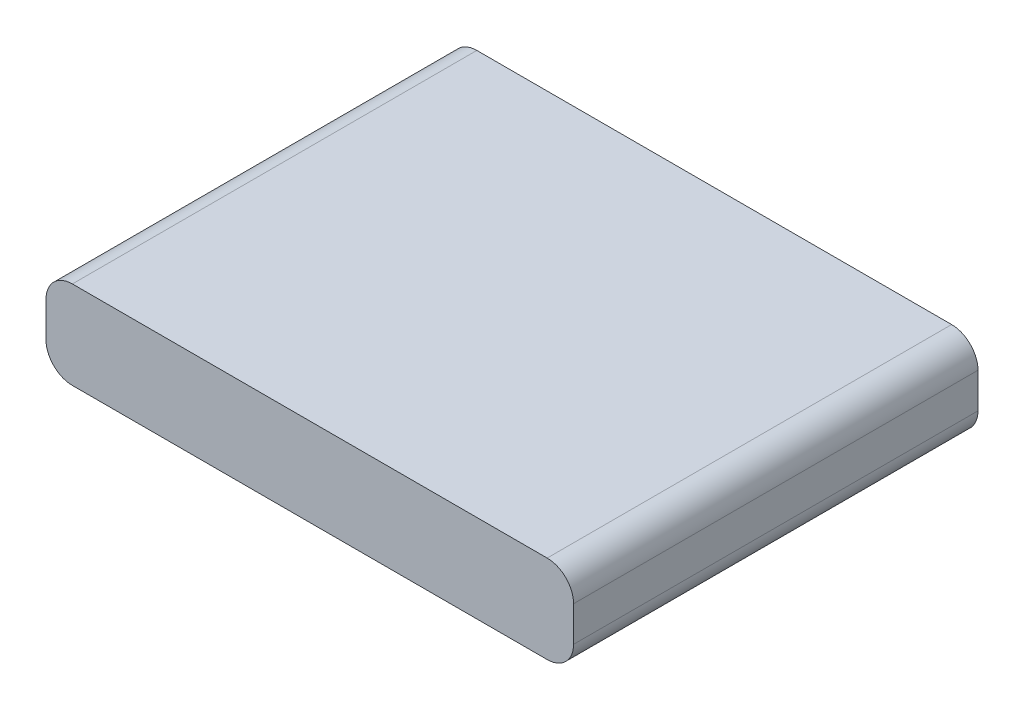
SolidWorks part; units mm, degrees
ref_plane "Front Plane" through (0, 0, 0) normal (0, 0, 1) x (1, 0, 0)
ref_plane "Top Plane" through (0, 0, 0) normal (0, 1, 0) x (1, 0, 0)
ref_plane "Right Plane" through (0, 0, 0) normal (1, 0, 0) x (0, 0, -1)
sketch "Sketch1" plane through (0, 0, 0) normal (0, 0, 1) x (1, 0, 0)
  line L0 (-27, 0) -> (27, 0)
  line L1 (30, 3) -> (30, 7)
  line L2 (27, 10) -> (-27, 10)
  line L3 (-30, 7) -> (-30, 3)
  arc A0 (27, 0) -> (30, 3) centre (27, 3) ccw
  arc A1 (30, 7) -> (27, 10) centre (27, 7) ccw
  arc A2 (-27, 10) -> (-30, 7) centre (-27, 7) ccw
  arc A3 (-30, 3) -> (-27, 0) centre (-27, 3) ccw
extrude "Boss-Extrude1" add sketch "Sketch1" along normal mid plane 46
sketch "Sketch2" plane through (0, 0, 0) normal (0, 1, 0) x (1, 0, 0)
  circle A0 centre (12, -17.5) radius 2
  circle A1 centre (-12, 17.5) radius 2
extrude "Cut-Extrude1" cut sketch "Sketch2" along normal blind 7.5
